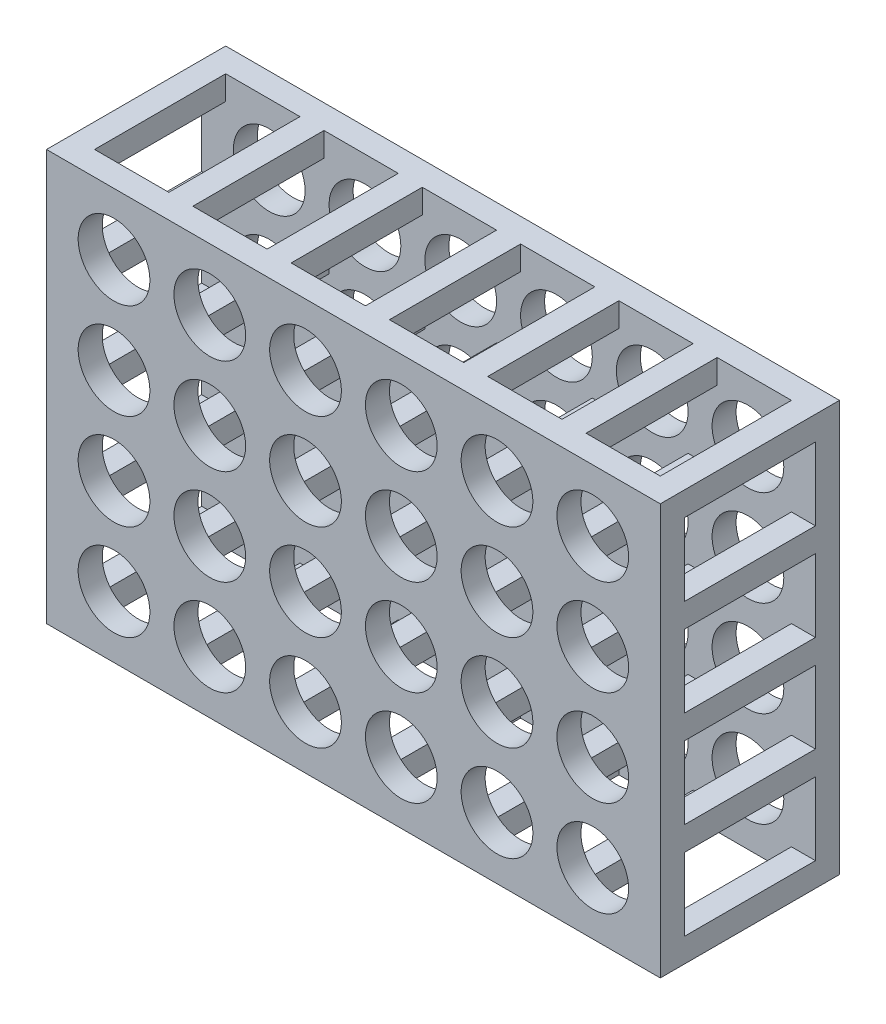
SolidWorks part; units mm, degrees
ref_plane "Front Plane" through (0, 0, 0) normal (0, 0, 1) x (1, 0, 0)
ref_plane "Top Plane" through (0, 0, 0) normal (0, 1, 0) x (1, 0, 0)
ref_plane "Right Plane" through (0, 0, 0) normal (1, 0, 0) x (0, 0, -1)
sketch "Sketch1" plane through (0, 0, 0) normal (0, 0, 1) x (1, 0, 0)
  line L1 (-54.6738, 25.2702) -> (73.0862, 25.2702)
  line L2 (-54.6738, 25.2702) -> (-54.6738, -60.2098)
  line L3 (-54.6738, -60.2098) -> (73.0862, -60.2098)
  line L4 (73.0862, 25.2702) -> (73.0862, -60.2098)
  dimension "D1" = 127.76
  dimension "D2" = 85.48
extrude "Boss-Extrude1" add sketch "Sketch1" along normal blind 5
sketch "Sketch2" plane through (0, 0, 5) normal (0, 0, 1) x (1, 0, 0)
  line L0 (-54.6738, 25.2702) -> (-54.6738, -60.2098) construction
  line L1 (73.0862, 25.2702) -> (-54.6738, 25.2702) construction
  circle A0 centre (-40.6188, 12.4252) radius 7.465
  dimension "D1" = 14.93
  dimension "D2" = 14.055
  dimension "D3" = 12.845
extrude "Cut-Extrude1" cut sketch "Sketch2" against normal through all
sketch "Sketch3" plane through (0, 0, 5) normal (0, 0, 1) x (1, 0, 0)
  line L1 (-54.6738, 25.2702) -> (-49.6738, 25.2702)
  line L2 (-54.6738, 25.2702) -> (-54.6738, 20.2702)
  line L3 (-54.6738, 20.2702) -> (-49.6738, 20.2702)
  line L4 (-49.6738, 25.2702) -> (-49.6738, 20.2702)
  dimension "D1" = 5
  dimension "D2" = 5
extrude "Boss-Extrude2" add sketch "Sketch3" along normal blind 13.65
pattern_linear "LPattern2" count 6 spacing 19.93 along (1, 0, 0) count 4 spacing 19.93 along (0, -1, 0) of "Cut-Extrude1"
pattern_linear "LPattern3" count 2 spacing 122.76 along (1, 0, 0) count 5 spacing 20.12 along (0, -1, 0) of "Boss-Extrude2"
pattern_linear "LPattern5" count 6 spacing 20.46 along (1, 0, 0) count 2 spacing 80.48 along (0, -1, 0) of "Boss-Extrude2"
sketch "Sketch4" plane through (0, 0, 5) normal (0, 0, 1) x (1, 0, 0)
  line L2 (-28.1538, -39.8998) -> (-33.1538, -39.8998)
  line L3 (-28.1538, -39.8998) -> (-28.1538, -34.8998)
  line L4 (-28.1538, -34.8998) -> (-33.1538, -34.8998)
  line L5 (-33.1538, -39.8998) -> (-33.1538, -34.8998)
  line L6 (-28.1538, -39.8998) -> (-33.1538, -34.8998) construction
  line L7 (-28.1538, -34.8998) -> (-33.1538, -39.8998) construction
  circle A1 centre (-20.6888, -47.3648) radius 7.465 construction
  circle A2 centre (-40.6188, -47.3648) radius 7.465 construction
  point P2 (-30.6538, -37.3998)
  dimension "D1" = 5
  dimension "D2" = 5
  dimension "D5" = 9.965
  dimension "D3" = 9.965
extrude "Boss-Extrude3" add sketch "Sketch4" along normal up to surface (13.65 mm away) up to face at (-52.1738, 2.6502, 18.65)
pattern_linear "LPattern4" count 5 spacing 19.93 along (1, 0, 0) count 3 spacing 19.93 along (0, 1, 0) of "Boss-Extrude3"
ref_plane "Plane1" through (0, 0, 18.65) normal (0, 0, -1) x (-1, 0, 0)
mirror "Mirror9" about plane through (0, 0, 18.65) normal (0, 0, -1) of bodies 111
equation "\"platewidth\"=127.76"
equation "\"D1@Sketch1\"=\"platewidth\""
equation "\"plateheight\"=85.48"
equation "\"D2@Sketch1\"=\"plateheight\""
equation "\"od\"= \"od_meas\" + \"od_offset\""
equation "\"height\"= \"height_overall\" - \"neck_offset\""
equation "\"spacing\" = 5"
equation "\"nx\"= int ( ( \"platewidth\" - \"spacing\" ) / ( \"od\" + \"spacing\" ) )'force spacing on left and right ends"
equation "\"ny\"= int ( ( \"plateheight\" - \"spacing\" ) / ( \"od\" + \"spacing\" ) )"
equation "\"xoff\" = ( \"platewidth\" - ( \"nx\" * \"od\" ) - ( \"nx\" - 1 ) * \"spacing\" ) / 2"
equation "\"yoff\"= ( \"plateheight\" - ( \"ny\" * \"od\" ) - ( \"ny\" - 1 ) * \"spacing\" ) / 2"
equation "\"od_offset\"= 0.2'extra width to print vial holes"
equation "\"od_meas\"= 14.73'measured vial outer dimension (mm)"
equation "\"neck_offset\"= 8'distance from top of threads to wide point of vial"
equation "\"height_overall\"= 45.3'overall height of vial"
equation "\"D3@Sketch2\"=\"yoff\" + (\"od\"/2)"
equation "\"D2@Sketch2\"= \"xoff\" + \"od\"/2"
equation "\"D1@Boss-Extrude2\"= (\"height\"/2) - 5"
equation "\"D1@LPattern2\"= \"nx\""
equation "\"D3@LPattern2\"= \"od\" + \"spacing\""
equation "\"D2@LPattern2\"= \"ny\""
equation "\"D4@LPattern2\"= \"od\" + \"spacing\""
equation "\"D3@LPattern3\"=(\"platewidth\"-5) "
equation "\"D4@LPattern3\"=(\"plateheight\"-5)/ \"ny\""
equation "\"D5@Sketch4\"= (\"od\" + \"spacing\")/2"
equation "\"D3@LPattern4\"= \"od\" + \"spacing\""
equation "\"D4@LPattern4\"= \"od\" + \"spacing\""
equation "\"D2@LPattern4\"= \"ny\" - 1"
equation "\"D2@LPattern3\"= \"ny\"+1"
equation "\"D1@LPattern3\"=2"
equation "\"D1@LPattern4\"= \"nx\"-1"
equation "\"D3@LPattern5\"=(\"platewidth\"-5)/(\"nx\")"
equation "\"D1@LPattern5\"= \"nx\""
equation "\"D4@LPattern5\"= \"plateheight\"-5"
equation "\"D3@Sketch4\"= (\"spacing\"+\"od\")/2"
